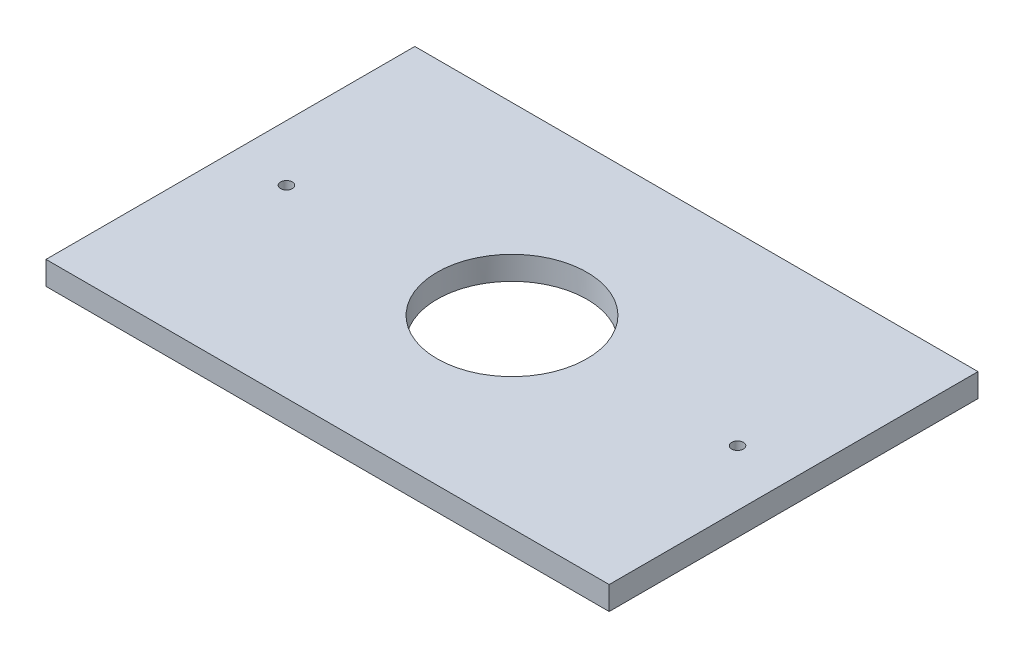
SolidWorks part; units mm, degrees
material "Oak"
ref_plane "Front Plane" through (0, 0, 0) normal (0, 0, 1) x (1, 0, 0)
ref_plane "Top Plane" through (0, 0, 0) normal (0, 1, 0) x (1, 0, 0)
ref_plane "Right Plane" through (0, 0, 0) normal (1, 0, 0) x (0, 0, -1)
sketch "Sketch1" plane through (0, 0, 0) normal (0, 1, 0) x (1, 0, 0)
  line L1 (0, 0) -> (152.7, 0)
  line L2 (0, 0) -> (0, 100)
  line L3 (0, 100) -> (152.7, 100)
  line L4 (152.7, 0) -> (152.7, 100)
  dimension "D1" = 152.7
  dimension "D2" = 100
extrude "Boss-Extrude1" add sketch "Sketch1" along normal blind 6.35
sketch "Sketch2" plane through (0, 6.35, 0) normal (0, 1, 0) x (1, 0, 0)
  line L0 (76.35, 100) -> (76.35, 0) construction
  line L1 (152.7, 100) -> (0, 100) construction
  line L2 (0, 0) -> (152.7, 0) construction
  line L3 (0, 50) -> (152.7, 50) construction
  line L4 (0, 100) -> (0, 0) construction
  line L5 (152.7, 0) -> (152.7, 100) construction
  circle A0 centre (76.35, 50) radius 20.32
  dimension "D1" = 40.64
extrude "Cut-Extrude1" cut sketch "Sketch2" against normal blind 10
sketch "Sketch3" plane through (0, 6.35, 0) normal (0, 1, 0) x (1, 0, 0)
  line L0 (0, 100) -> (0, 0) construction
  line L1 (152.7, 100) -> (0, 100) construction
  line L3 (152.7, 0) -> (152.7, 100) construction
  circle A0 centre (15.2, 50) radius 1.5875
  circle A1 centre (137.5, 50) radius 1.5875
  point P0 (0, 50)
  point P1 (76.35, 100)
  point P4 (15.2, 50)
  point P7 (137.5, 50)
  dimension "D1" = 3.175
  dimension "D2" = 3.175
  dimension "D3" = 15.2
  dimension "D4" = 15.2
  dimension "D5" = 50
  dimension "D6" = 50
extrude "Cut-Extrude2" cut sketch "Sketch3" against normal blind 10
